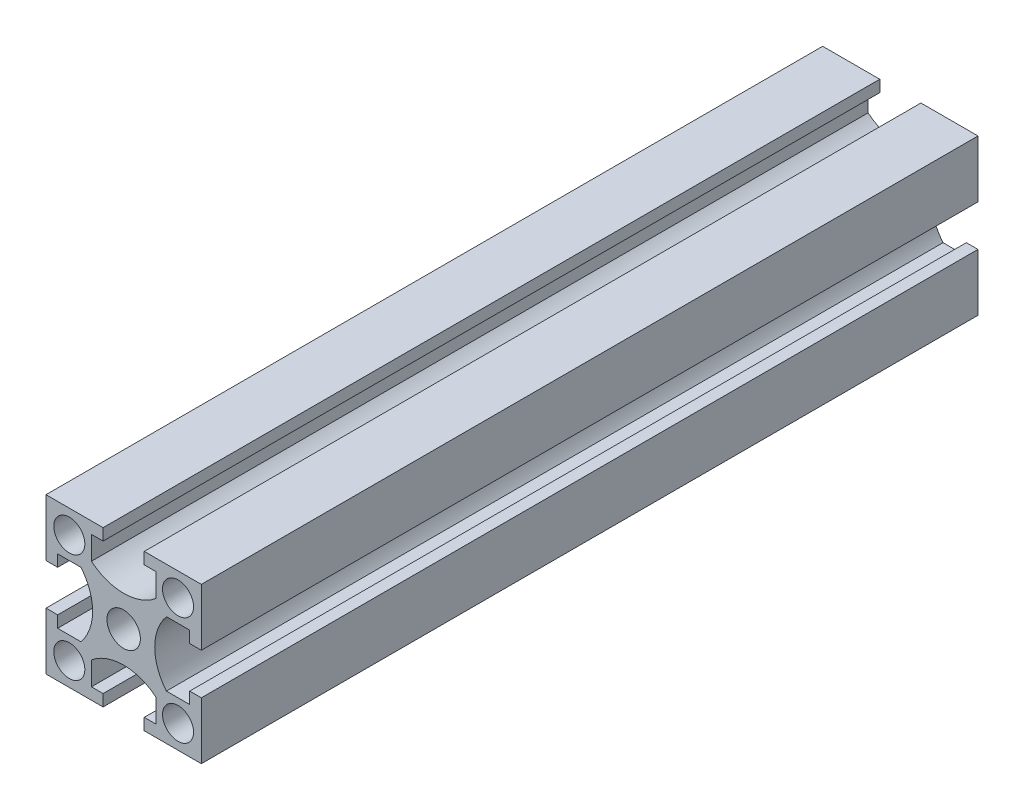
SolidWorks part; units mm, degrees
material "6061-T6 (SS)"
ref_plane "정면" through (0, 0, 0) normal (0, 0, 1) x (1, 0, 0)
ref_plane "윗면" through (0, 0, 0) normal (0, 1, 0) x (1, 0, 0)
ref_plane "우측면" through (0, 0, 0) normal (1, 0, 0) x (0, 0, -1)
sketch "스케치1" plane through (0, 0, 0) normal (0, 0, 1) x (1, 0, 0)
  line L1 (-10, 10) -> (10, 10)
  line L2 (-10, 10) -> (-10, -10)
  line L3 (-10, -10) -> (10, -10)
  line L4 (10, 10) -> (10, -10)
  line L5 (-10, 10) -> (10, -10) construction
  line L6 (-10, -10) -> (10, 10) construction
  point P0 (0, 0)
  dimension "D1" = 20
  dimension "D2" = 20
extrude "보스-돌출1" add sketch "스케치1" along normal blind 100
sketch "스케치2" plane through (0, 0, 100) normal (0, 0, 1) x (1, 0, 0)
  line L0 (-2.65, 10) -> (-2.65, 8.5)
  line L1 (10, 10) -> (-10, 10) construction
  line L2 (-2.65, 8.5) -> (-4.15, 8.5)
  line L3 (-4.15, 8.5) -> (-4.15, 5.5)
  line L4 (-2.65, 10) -> (2.65, 10)
  line L5 (2.65, 10) -> (2.65, 8.5)
  line L6 (2.65, 8.5) -> (4.15, 8.5)
  line L7 (4.15, 8.5) -> (4.15, 5.5)
  line L8 (10, 2.65) -> (8.5, 2.65)
  line L9 (8.5, 2.65) -> (8.5, 4.15)
  line L10 (8.5, 4.15) -> (5.5, 4.15)
  line L11 (10, 2.65) -> (10, -2.65)
  line L12 (10, -2.65) -> (8.5, -2.65)
  line L13 (8.5, -2.65) -> (8.5, -4.15)
  line L14 (8.5, -4.15) -> (5.5, -4.15)
  line L15 (2.65, -10) -> (2.65, -8.5)
  line L16 (2.65, -8.5) -> (4.15, -8.5)
  line L17 (4.15, -8.5) -> (4.15, -5.5)
  line L18 (2.65, -10) -> (-2.65, -10)
  line L19 (-2.65, -10) -> (-2.65, -8.5)
  line L20 (-2.65, -8.5) -> (-4.15, -8.5)
  line L21 (-4.15, -8.5) -> (-4.15, -5.5)
  line L22 (-10, -2.65) -> (-8.5, -2.65)
  line L23 (-8.5, -2.65) -> (-8.5, -4.15)
  line L24 (-8.5, -4.15) -> (-5.5, -4.15)
  line L25 (-10, -2.65) -> (-10, 2.65)
  line L26 (-10, 2.65) -> (-8.5, 2.65)
  line L27 (-8.5, 2.65) -> (-8.5, 4.15)
  line L28 (-8.5, 4.15) -> (-5.5, 4.15)
  arc A1 (-4.15, 5.5) -> (4.15, 5.5) centre (0, 10.4908) ccw
  arc A2 (5.5, 4.15) -> (5.5, -4.15) centre (10.4908, 0) ccw
  arc A3 (4.15, -5.5) -> (-4.15, -5.5) centre (0, -10.4908) ccw
  arc A4 (-5.5, -4.15) -> (-5.5, 4.15) centre (-10.4908, 0) ccw
  circle A5 centre (0, 0) radius 2.15
  circle A6 centre (-7, 7) radius 2
  circle A7 centre (7, 7) radius 2
  circle A8 centre (7, -7) radius 2
  circle A9 centre (-7, -7) radius 2
  point P4 (-2.65, 9.25)
  point P43 (0, 0)
  dimension "D2" = 1.5
  dimension "D8" = 4.3
  dimension "D9" = 4
  dimension "D10" = 4
  dimension "D11" = 4
  dimension "D12" = 4
  dimension "D1" = 5.3
  dimension "D3" = 8.3
  dimension "D4" = 4.15
  dimension "D5" = 2.65
  dimension "D6" = 4
  dimension "D7" = 3
  dimension "D13" = 14
  dimension "D14" = 7
  dimension "D15" = 7
  dimension "D16" = 7
  dimension "D17" = 14
  dimension "D18" = 7
  dimension "D19" = 7
  dimension "D20" = 7
extrude "컷-돌출1" cut sketch "스케치2" against normal through all
sketch "스케치3" plane through (0, 10, 0) normal (0, 1, 0) x (1, 0, 0)
  line L0 (-6.1791, -89.5262) -> (-6.1791, -148.9088) construction
  text T0 "up"
